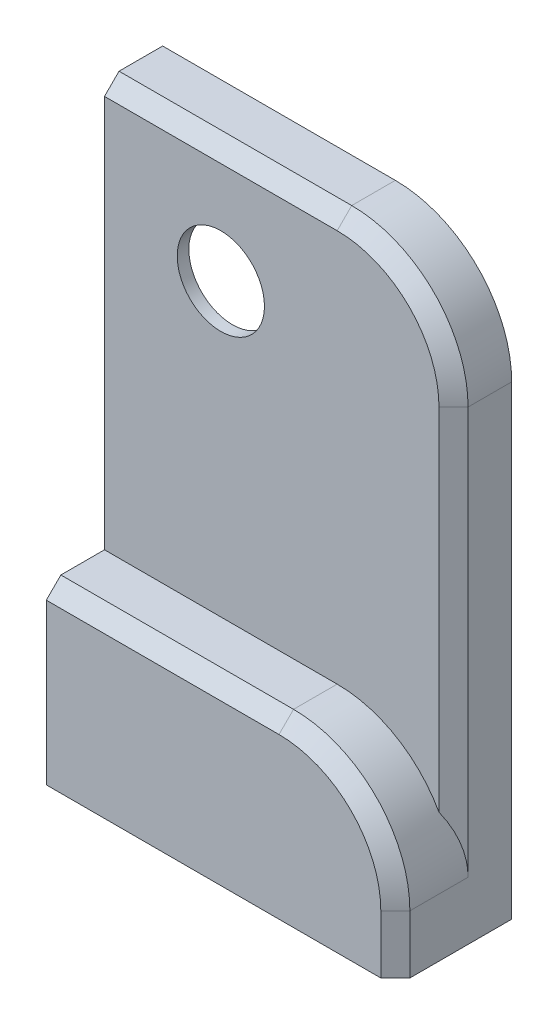
SolidWorks part; units mm, degrees
ref_plane "Front Plane" through (0, 0, 0) normal (0, 0, 1) x (1, 0, 0)
ref_plane "Top Plane" through (0, 0, 0) normal (0, 1, 0) x (1, 0, 0)
ref_plane "Right Plane" through (0, 0, 0) normal (1, 0, 0) x (0, 0, -1)
sketch "Sketch1" plane through (0, 0, 0) normal (0, 0, 1) x (1, 0, 0)
  line L1 (0, 0) -> (-76.2, 0)
  line L2 (0, 0) -> (0, -127)
  line L3 (0, -127) -> (-76.2, -127)
  line L4 (-76.2, 0) -> (-76.2, -127)
  dimension "D1" = 127
  dimension "D2" = 76.2
extrude "Boss-Extrude1" add sketch "Sketch1" along normal blind 12.7
sketch "Sketch2" plane through (0, 0, 12.7) normal (0, 0, 1) x (1, 0, 0)
  line L0 (0, -127) -> (0, 0) construction
  line L1 (-76.2, -127) -> (0, -127)
  line L2 (-76.2, -127) -> (-76.2, -88.9)
  line L3 (-76.2, -88.9) -> (0, -88.9)
  line L4 (0, -127) -> (0, -88.9)
  dimension "D1" = 38.1
extrude "Boss-Extrude2" add sketch "Sketch2" along normal blind 12.7
sketch "Sketch3" plane through (0, 0, 12.7) normal (0, 0, 1) x (1, 0, 0)
  line L0 (0, 0) -> (-76.2, 0) construction
  line L1 (-76.2, 0) -> (-76.2, -88.9) construction
  circle A0 centre (-50.8, -25.4) radius 9.525
  point P2 (-60.6198, -15.8467)
  point P3 (0, 0)
  point P8 (0, 0)
  point P9 (0, 0)
  point P10 (0, 0)
  point P11 (0, 0)
  point P12 (0, 0)
  point P13 (0, 0)
  point P14 (0, 0)
  dimension "D3" = 19.05
  dimension "D1" = 25.4
  dimension "D2" = 25.4
extrude "Cut-Extrude1" cut sketch "Sketch3" against normal through all contours A0
fillet "Fillet1" radius 25.4 2 edges at (0, -88.9, 19.05) (0, 0, 6.35)
chamfer "Chamfer1" distance 3.175 angle 45 6 edges at (0, -120.65, 25.4) (-7.4395, -96.3395, 25.4) (-50.8, -88.9, 25.4) (0, -69.85, 12.7) (-7.4395, -7.4395, 12.7) (-50.8, 0, 12.7)
shell "Shell1" thickness 2.54
